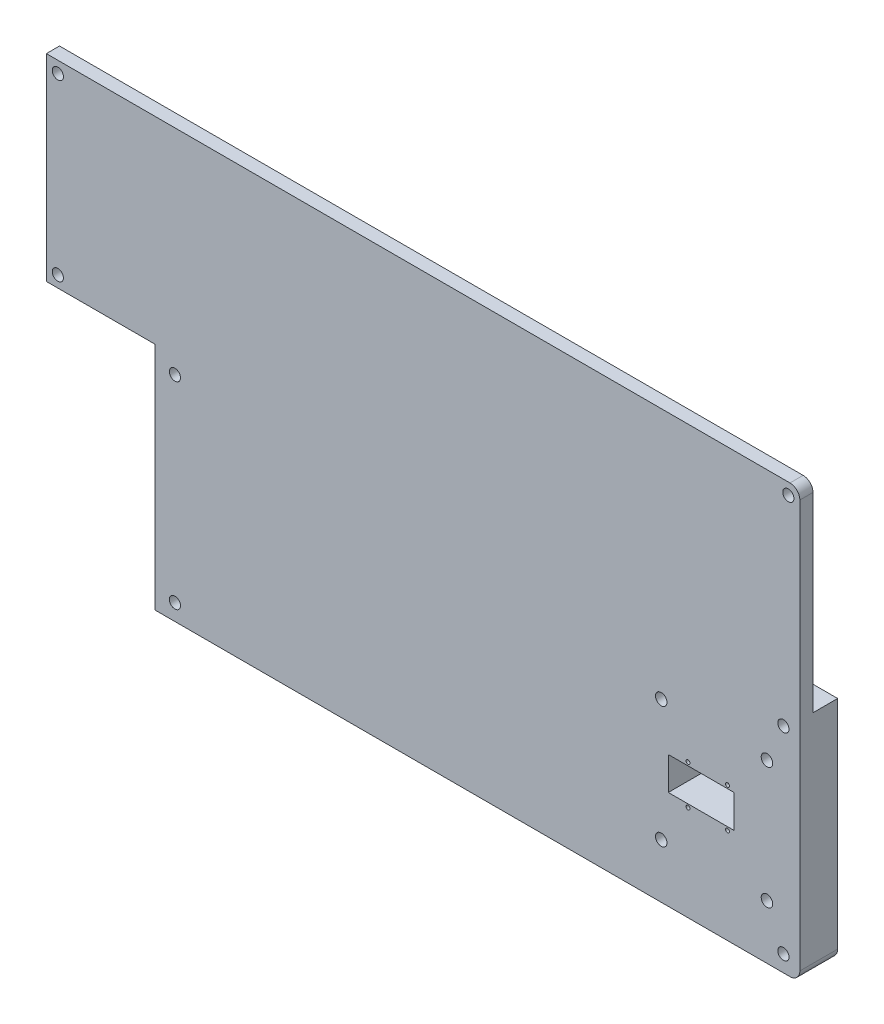
SolidWorks part; units mm, degrees
ref_plane "正面" through (0, 0, 0) normal (0, 0, 1) x (1, 0, 0)
ref_plane "平面" through (0, 0, 0) normal (0, 1, 0) x (1, 0, 0)
ref_plane "右側面" through (0, 0, 0) normal (1, 0, 0) x (0, 0, -1)
sketch "ｽｹｯﾁ1" plane through (0, 0, 0) normal (0, 0, 1) x (1, 0, 0)
  line L1 (0, 0) -> (196, 0)
  line L2 (0, 0) -> (0, 130)
  line L3 (0, 130) -> (196, 130)
  line L4 (196, 0) -> (196, 130)
  dimension "D1" = 130
  dimension "D2" = 196
extrude "ﾎﾞｽ - 押し出し1" add sketch "ｽｹｯﾁ1" along normal blind 4
sketch "ｽｹｯﾁ3" plane through (0, 0, 0) normal (0, 0, -1) x (-1, 0, 0)
  line L0 (0, 130) -> (0, 0) construction
  line L1 (-196, 0) -> (0, 0)
  line L2 (-196, 0) -> (-196, 69)
  line L3 (-196, 69) -> (0, 69)
  line L4 (0, 0) -> (0, 69)
  dimension "D1" = 69
extrude "ﾎﾞｽ - 押し出し2" add sketch "ｽｹｯﾁ3" along normal blind 7.5
sketch "ｽｹｯﾁ4" plane through (0, 0, 0) normal (-1, 0, 0) x (0, 0, 1)
  line L0 (0, 130) -> (0, 69) construction
  line L1 (4, 130) -> (0, 130)
  line L2 (4, 130) -> (4, 70)
  line L3 (4, 70) -> (0, 70)
  line L4 (0, 130) -> (0, 70)
  dimension "D1" = 60
extrude "ﾎﾞｽ - 押し出し3" add sketch "ｽｹｯﾁ4" along normal blind 33.1
sketch "ｽｹｯﾁ2" plane through (0, 0, 4) normal (0, 0, 1) x (1, 0, 0)
  line L0 (196, 0) -> (196, 130) construction
  line L1 (0, 0) -> (196, 0) construction
  line L2 (196, 130) -> (-33.1, 130) construction
  circle A0 centre (191, 5) radius 1.7
  circle A1 centre (192.5, 126.5) radius 1.7
  circle A2 centre (191, 65) radius 1.7
  circle A3 centre (6, 5) radius 1.7
  circle A4 centre (6, 65) radius 1.7
  dimension "D3" = 3.4
  dimension "D6" = 3.4
  dimension "D7" = 3.4
  dimension "D9" = 60
  dimension "D10" = 185
  dimension "D11" = 3.4
  dimension "D13" = 3.4
  dimension "D15" = 60
  dimension "D1" = 5
  dimension "D2" = 5
  dimension "D4" = 3.5
  dimension "D5" = 3.5
  dimension "D8" = 5
  dimension "D12" = 5
  dimension "D14" = 185
extrude "ｶｯﾄ - 押し出し1" cut sketch "ｽｹｯﾁ2" against normal through all
sketch "ｽｹｯﾁ5" plane through (0, 0, 4) normal (0, 0, 1) x (1, 0, 0)
  line L0 (196, 130) -> (-33.1, 130) construction
  line L1 (-33.1, 70) -> (0, 70) construction
  line L2 (-33.1, 70) -> (-33.1, 130) construction
  circle A0 centre (-29.6, 126.5) radius 1.7
  circle A1 centre (-29.6, 73.5) radius 1.7
  dimension "D1" = 3.4
  dimension "D2" = 3.4
  dimension "D3" = 3.5
  dimension "D4" = 3.5
  dimension "D5" = 3.5
  dimension "D6" = 3.5
extrude "ｶｯﾄ - 押し出し2" cut sketch "ｽｹｯﾁ5" against normal through all
fillet "ﾌｨﾚｯﾄ1" radius 3 2 edges at (196, 0, -1.75) (196, 130, 2)
sketch "ｽｹｯﾁ7" plane through (0, 0, 4) normal (0, 0, 1) x (1, 0, 0)
  line L0 (0, 0) -> (193, 0) construction
  line L1 (176, 30) -> (156, 30)
  line L2 (176, 30) -> (176, 40)
  line L3 (176, 40) -> (156, 40)
  line L4 (156, 30) -> (156, 40)
  line L5 (196, 3) -> (196, 127) construction
  circle A0 centre (174, 41) radius 0.6
  circle A1 centre (162, 41) radius 0.6
  circle A2 centre (174, 29) radius 0.6
  circle A3 centre (162, 29) radius 0.6
  dimension "D5" = 1.2
  dimension "D6" = 1.2
  dimension "D7" = 1.2
  dimension "D8" = 1.2
  dimension "D16" = 1
  dimension "D1" = 10
  dimension "D2" = 20
  dimension "D3" = 30
  dimension "D4" = 20
  dimension "D9" = 12
  dimension "D10" = 12
  dimension "D11" = 12
  dimension "D12" = 12
  dimension "D13" = 2
  dimension "D14" = 2
  dimension "D15" = 1
extrude "ｶｯﾄ - 押し出し3" cut sketch "ｽｹｯﾁ7" against normal through all
sketch "ｽｹｯﾁ8" plane through (0, 0, 4) normal (0, 0, 1) x (1, 0, 0)
  line L0 (196, 3) -> (196, 127) construction
  line L1 (176, 40) -> (156, 40) construction
  circle A0 centre (186, 53.5) radius 1.75
  circle A1 centre (153.85, 53.5) radius 1.75
  circle A2 centre (153.85, 16.5) radius 1.75
  circle A3 centre (186, 16.5) radius 1.75
  point P8 (0, 0)
  dimension "D1" = 3.5
  dimension "D2" = 3.5
  dimension "D3" = 3.5
  dimension "D4" = 3.5
  dimension "D7" = 37
  dimension "D5" = 10
  dimension "D6" = 10
  dimension "D8" = 37
  dimension "D9" = 32.15
  dimension "D10" = 32.15
  dimension "D11" = 13.5
  dimension "D12" = 13.5
extrude "ｶｯﾄ - 押し出し4" cut sketch "ｽｹｯﾁ8" against normal blind 40
